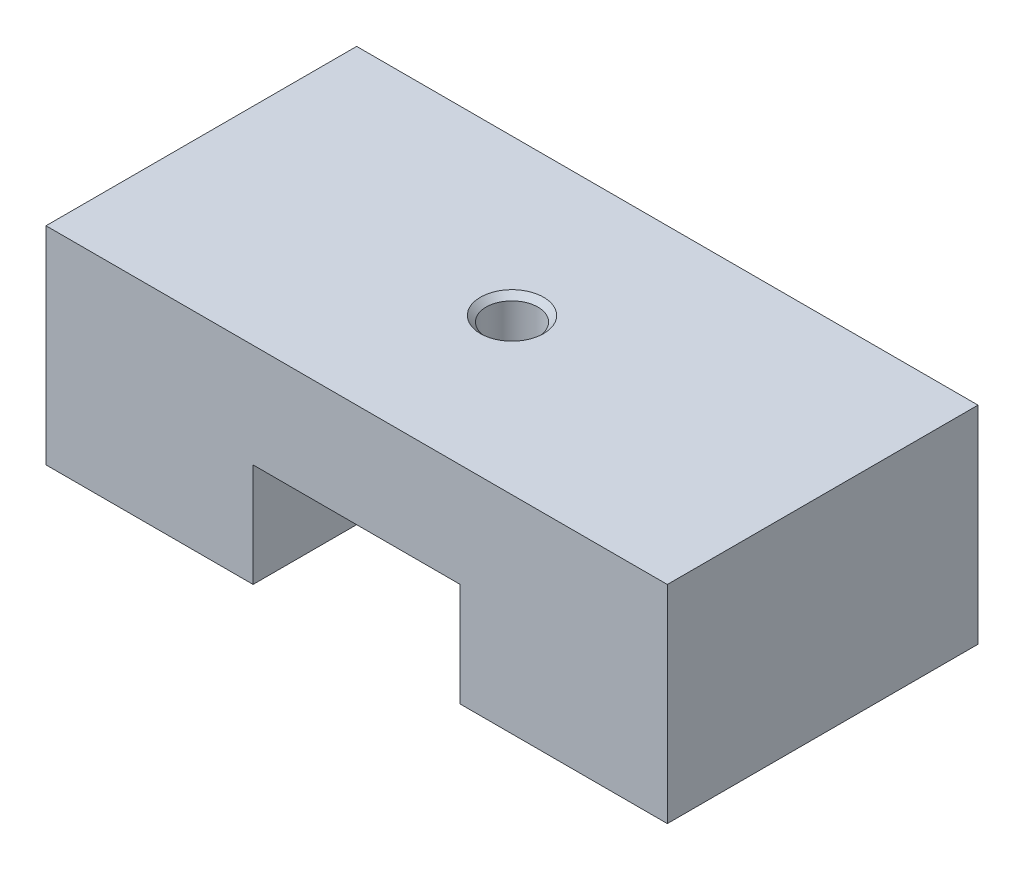
SolidWorks part; units mm, degrees
ref_plane "Front Plane" through (0, 0, 0) normal (0, 0, 1) x (1, 0, 0)
ref_plane "Top Plane" through (0, 0, 0) normal (0, 1, 0) x (1, 0, 0)
ref_plane "Right Plane" through (0, 0, 0) normal (1, 0, 0) x (0, 0, -1)
sketch "Sketch1" plane through (0, 0, 0) normal (0, 0, 1) x (1, 0, 0)
  line L0 (-15, 0) -> (15, 0)
  line L1 (0, 0) -> (0, -6.3053) construction
  line L2 (-15, 0) -> (-15, -10)
  line L3 (-15, -10) -> (-5, -10)
  line L4 (-5, -10) -> (-5, -5)
  line L5 (-5, -5) -> (5, -5)
  line L6 (5, -10) -> (5, -5)
  line L7 (15, -10) -> (5, -10)
  line L8 (15, 0) -> (15, -10)
  point P4 (0, 0)
  point P12 (0, -5)
  dimension "D1" = 30
  dimension "D2" = 10
  dimension "D3" = 5
  dimension "D4" = 10
extrude "Boss-Extrude1" add sketch "Sketch1" along normal blind 15
sketch "Sketch2" plane through (0, 0, 0) normal (0, 1, 0) x (1, 0, 0)
  line L0 (-15, -15) -> (15, 0) construction
  line L1 (-15, 0) -> (15, -15) construction
  circle A0 centre (0, -7.5) radius 1.9117
hole_wizard "M3x0.5 Tapped Hole1" positions "Sketch3" profile "Sketch4" tap size "M3x0.5" standard "ANSI Metric" end condition through all
sketch "Sketch3" plane through (0, 0, 0) normal (0, 1, 0) x (1, 0, 0)
  point P0 (0, -7.5)
sketch "Sketch4" plane through (0, 0, 7.5) normal (1, 0, 0) x (0, 0, 1)
  line L0 (0, 0) -> (0, 10)
  line L1 (0, 10) -> (1.25, 10)
  line L2 (1.25, 10) -> (1.25, 0.275)
  line L3 (1.25, 0.275) -> (1.525, 0)
  line L5 (1.525, 0) -> (0, 0)
  line L6 (-1.25, 0.275) -> (-1.525, 0) construction
  line L11 (0, -6.35) -> (0, 107.95) construction
  dimension "Thread Major Dia." = 2.5
  dimension "Thru Tap Drill Depth" = 10
  dimension "Near C'Sink Dia." = 3.05
  dimension "Near C'Sink Angle" = 90
